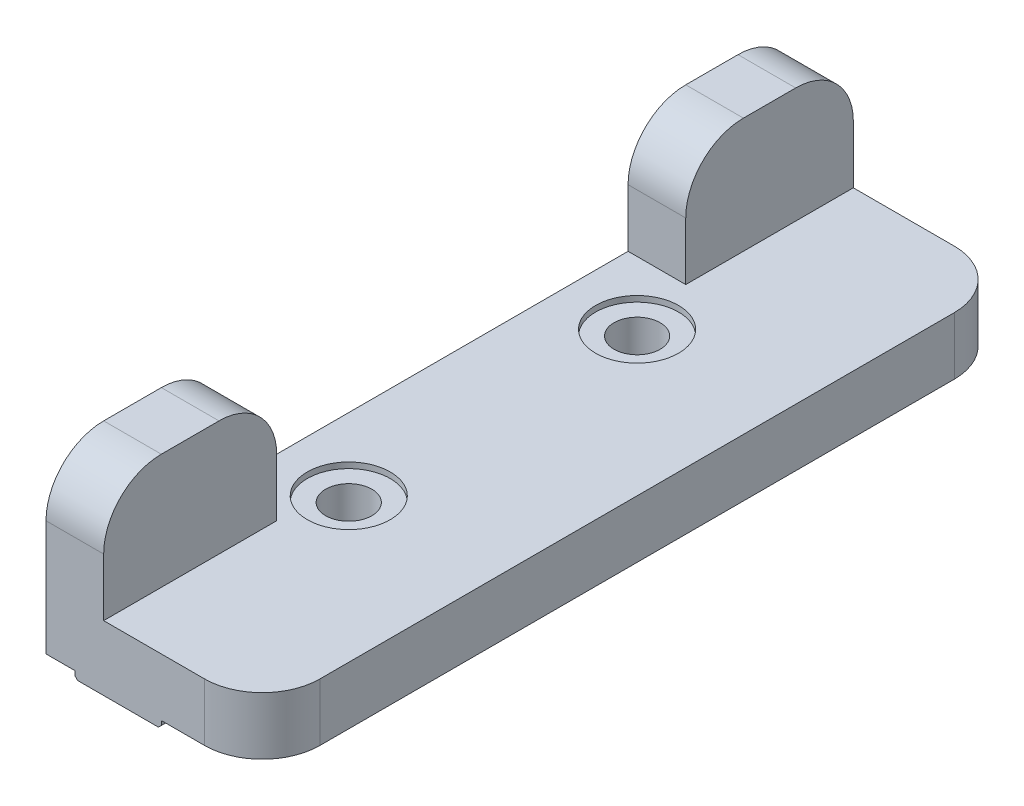
SolidWorks part; units mm, degrees
ref_plane "Front Plane" through (0, 0, 0) normal (0, 0, 1) x (1, 0, 0)
ref_plane "Top Plane" through (0, 0, 0) normal (0, 1, 0) x (1, 0, 0)
ref_plane "Right Plane" through (0, 0, 0) normal (1, 0, 0) x (0, 0, -1)
sketch "Sketch1" plane through (0, 0, 0) normal (0, 0, 1) x (1, 0, 0)
  line L0 (0, 0) -> (0, 12)
  line L1 (0, 0) -> (15, 0)
  line L3 (4, 4) -> (15, 4)
  line L4 (15, 0) -> (15, 4)
  line L7 (0, 12) -> (4, 12)
  line L8 (4, 4) -> (4, 12)
  dimension "D1" = 15
  dimension "D2" = 12
  dimension "D3" = 4
  dimension "D4" = 4
extrude "Boss-Extrude1" add sketch "Sketch1" along normal blind 52
sketch "Sketch5" plane through (0, 0, 0) normal (0, -1, 0) x (1, 0, 0)
  line L0 (0, 52) -> (15, 52) construction
  line L1 (8, 52) -> (2, 52)
  line L2 (8, 52) -> (8, 0)
  line L3 (8, 0) -> (2, 0)
  line L4 (2, 52) -> (2, 0)
  line L5 (0, 0) -> (15, 0) construction
  line L6 (5, 52) -> (5, 0) construction
  line L7 (15, 52) -> (15, 0) construction
  dimension "D1" = 6
  dimension "D2" = 10
extrude "Boss-BottomAlign" add sketch "Sketch5" along normal blind 0.5
fillet "Fillet1" radius 0.2 2 edges at (2, -0.5, 26) (8, -0.5, 26) profile chamfer
sketch "Sketch3" plane through (0, -0.5, 0) normal (0, -1, 0) x (1, 0, 0)
  line L2 (15, 52) -> (15, 0) construction
  line L3 (2.2, 26) -> (7.8, 26) construction
  line L4 (2.2, 52) -> (2.2, 0) construction
  line L5 (7.8, 0) -> (7.8, 52) construction
  circle A0 centre (5, 36) radius 1.6
  circle A1 centre (5, 16) radius 1.6
  point P15 (6, 16.9544)
  dimension "D1" = 3.2
  dimension "D2" = 10
  dimension "D3" = 10
extrude "Cut-BottomHole" cut sketch "Sketch3" against normal up to next
sketch "Sketch7" plane through (0, 4, 0) normal (0, 1, 0) x (1, 0, 0)
  circle A0 centre (5, -36) radius 2.875
  circle A1 centre (5, -16) radius 2.875
  dimension "D1" = 5.75
extrude "Cut-Extrude6" cut sketch "Sketch7" against normal blind 0.4 contours A0 | A1
sketch "Sketch6" plane through (0, 0, 0) normal (-1, 0, 0) x (0, 0, 1)
  line L1 (52, 0) -> (0, 0) construction
  line L3 (26, 12) -> (26, 0) construction
  line L4 (52, 0) -> (0, 0) construction
  line L7 (0, 12) -> (0, 0) construction
  circle A0 centre (6, 6) radius 3
  circle A1 centre (46, 6) radius 3
  point P10 (0, 0)
  point P12 (0, 0)
  point P16 (0, 2.8697)
  dimension "D1" = 6
  dimension "D2" = 6
  dimension "D3" = 6
extrude "Cut-Magnet" cut sketch "Sketch6" against normal blind 3
sketch "Sketch8" plane through (4, 0, 0) normal (1, 0, 0) x (0, 0, -1)
  line L0 (-13.3045, 4) -> (0, 4) construction
  line L1 (-11.6255, 4) -> (-40, 4)
  line L2 (-11.6255, 4) -> (-11.6255, 12)
  line L3 (-11.6255, 12) -> (-40, 12)
  line L4 (-40, 4) -> (-40, 12)
  line L5 (-52, 12) -> (-37.249, 12) construction
  line L6 (-25.8127, 4) -> (-25.8127, 12) construction
  line L7 (-52, 4) -> (-52, 12) construction
  dimension "D1" = 12
extrude "Cut-Extrude7" cut sketch "Sketch8" against normal up to next
fillet "Fillet2" radius 4 4 edges at (2, 12, 52) (2, 12, 40) (2, 12, 11.6255) (2, 12, 0)
fillet "Fillet3" radius 4 2 edges at (15, 2, 52) (15, 2, 0)
